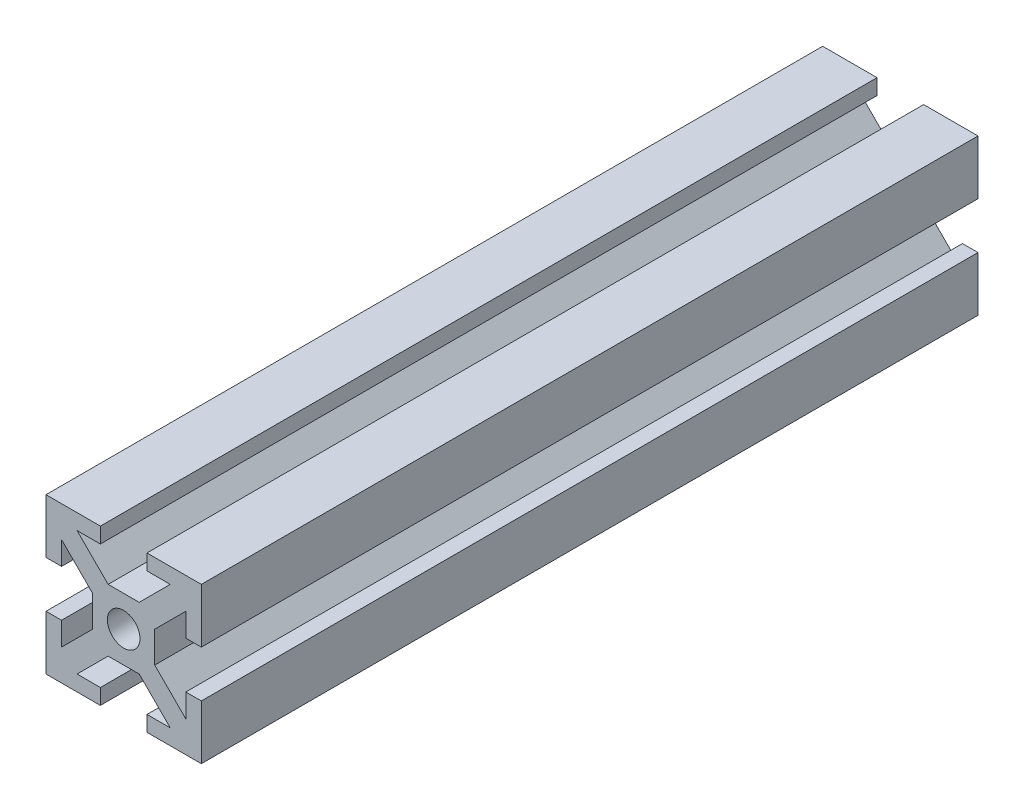
SolidWorks part; units mm, degrees
ref_plane "Front Plane" through (0, 0, 0) normal (0, 0, 1) x (1, 0, 0)
ref_plane "Top Plane" through (0, 0, 0) normal (0, 1, 0) x (1, 0, 0)
ref_plane "Right Plane" through (0, 0, 0) normal (1, 0, 0) x (0, 0, -1)
sketch "Sketch1" plane through (0, 0, 0) normal (0, 0, 1) x (1, 0, 0)
  line L0 (2, 4) -> (2, 7)
  line L9 (0, 0) -> (7, 0)
  line L10 (0, 0) -> (0, 7)
  line L14 (6, 14) -> (6, 6)
  line L15 (6, 6) -> (14, 6)
  line L19 (4, 2) -> (7, 2)
  line L20 (0, 10) -> (20, 10) construction
  line L21 (10, 20) -> (10, 0) construction
  line L22 (0, 7) -> (2, 7)
  line L23 (6, 8) -> (2, 4)
  line L24 (8, 6) -> (4, 2)
  line L25 (0, 0) -> (0, 20) construction
  line L26 (7, 2) -> (7, 0)
  line L27 (2, 2) -> (2, 18) construction
  line L28 (6, 14) -> (14, 14)
  line L29 (2, 2) -> (18, 2) construction
  line L30 (0, 0) -> (20, 0) construction
  line L31 (18, 2) -> (18, 18) construction
  line L32 (20, 0) -> (20, 20) construction
  line L33 (2, 18) -> (18, 18) construction
  line L34 (0, 20) -> (20, 20) construction
  line L35 (7, 18) -> (7, 20)
  line L36 (8, 14) -> (4, 18)
  line L37 (6, 12) -> (2, 16)
  line L38 (0, 13) -> (2, 13)
  line L39 (4, 18) -> (7, 18)
  line L40 (0, 20) -> (0, 13)
  line L41 (0, 20) -> (7, 20)
  line L42 (2, 16) -> (2, 13)
  line L43 (18, 16) -> (18, 13)
  line L44 (20, 20) -> (13, 20)
  line L45 (20, 20) -> (20, 13)
  line L46 (16, 18) -> (13, 18)
  line L47 (20, 13) -> (18, 13)
  line L48 (14, 12) -> (18, 16)
  line L49 (12, 14) -> (16, 18)
  line L50 (13, 18) -> (13, 20)
  line L51 (13, 2) -> (13, 0)
  line L52 (12, 6) -> (16, 2)
  line L53 (14, 8) -> (18, 4)
  line L54 (20, 7) -> (18, 7)
  line L55 (16, 2) -> (13, 2)
  line L56 (14, 14) -> (14, 6)
  line L57 (20, 0) -> (20, 7)
  line L58 (20, 0) -> (13, 0)
  line L59 (18, 4) -> (18, 7)
  circle A1 centre (10, 10) radius 2.1
  point P24 (0, 7)
  point P25 (2, 7)
  point P28 (10, 6)
  point P31 (6, 10)
  point P42 (10, 14)
  point P60 (14, 10)
  dimension "D5" = 3
  dimension "D3" = 4.2
  dimension "D7" = 2.1
  dimension "D1" = 20
  dimension "D4" = 2
  dimension "D6" = 3
  dimension "D8" = 4
  dimension "D9" = 4
  dimension "D10" = 10
  dimension "D11" = 10
  dimension "D12" = 10
  dimension "D13" = 10
  dimension "D14" = 6
  dimension "D15" = 45
  dimension "D16" = 6
  dimension "D17" = 45
extrude "Boss-Extrude1" add sketch "Sketch1" along normal blind 100 contours L42 L37 L14 L28 L36 L39 L35 L41 L40 L38 | L28 L56 L48 L43 L47 L45 L44 L50 L46 L49 | L56 L28 L14 L15 A1 | L26 L19 L24 L15 L14 L23 L0 L22 L10 L9 | L59 L53 L56 L15 L52 L55 L51 L58 L57 L54
